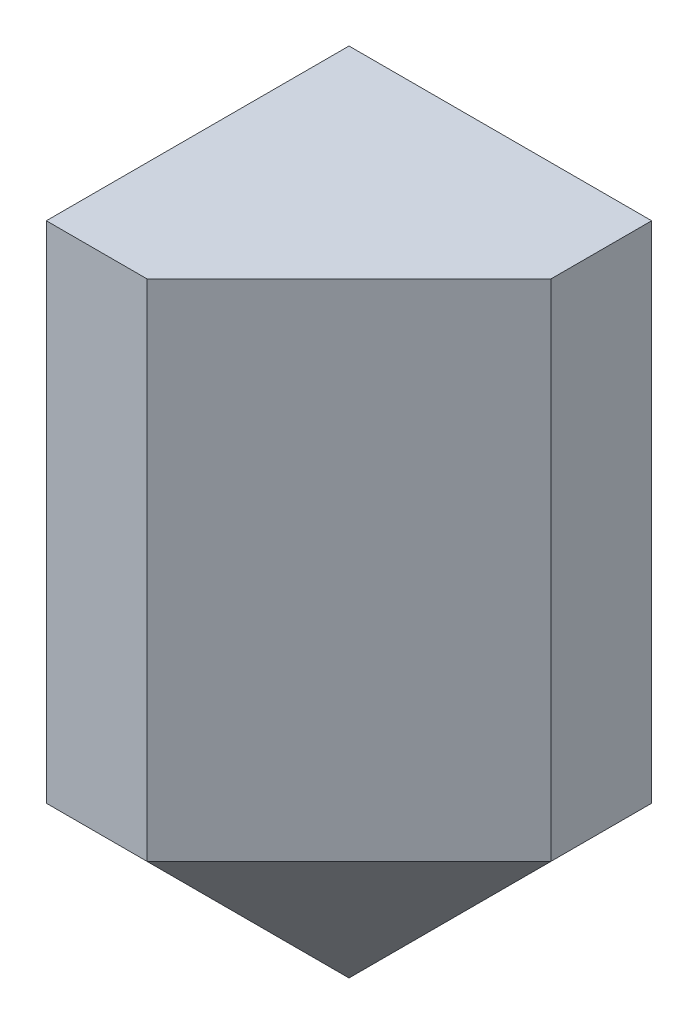
SolidWorks part; units mm, degrees
material "ABS"
ref_plane "Piano frontale" through (0, 0, 0) normal (0, 0, 1) x (1, 0, 0)
ref_plane "Piano superiore" through (0, 0, 0) normal (0, 1, 0) x (1, 0, 0)
ref_plane "Piano destro" through (0, 0, 0) normal (1, 0, 0) x (0, 0, -1)
sketch "Schizzo1" plane through (0, 0, 0) normal (0, 0, 1) x (1, 0, 0)
  line L1 (0, 0) -> (30, 0)
  line L2 (0, 0) -> (0, 40)
  line L3 (0, 40) -> (30, 40)
  line L4 (30, 0) -> (30, 40)
  dimension "D1" = 30
  dimension "D2" = 40
extrude "Estrusione-Estrusione1" add sketch "Schizzo1" along normal blind 30
chamfer "Smusso1" distance 20 angle 45 3 edges at (30, 20, 30) (30, 0, 15) (15, 0, 30)
sketch "Schizzo2" plane through (0, 40, 0) normal (0, 1, 0) x (1, 0, 0)
  line L0 (0, 0) -> (30, 0)
  line L1 (30, 0) -> (30, -10)
  line L2 (30, -10) -> (10, -30)
  line L3 (10, -30) -> (0, -30)
  line L4 (0, -30) -> (0, 0)
extrude "Estrusione-Estrusione2" add sketch "Schizzo2" along normal blind 30
hole_wizard "Foro per Vite M5-1" positions "Schizzo3" profile "Schizzo4" hole size "M5" standard "ISO"
sketch "Schizzo3" plane through (0, 0, 0) normal (-1, 0, 0) x (0, 0, 1)
  line L0 (14, 20) -> (14, 34) construction
  line L2 (0, 70) -> (0, 0) construction
  line L4 (14, 48) -> (14, 34) construction
  line L5 (0, 70) -> (30, 70) construction
  point P0 (14, 20)
  point P28 (14, 48)
  dimension "D1" = 14
  dimension "D2" = 22
  dimension "D3" = 14
  dimension "D4" = 14
sketch "Schizzo4" plane through (0, 20, 14) normal (0, 1, 0) x (0, 0, 1)
  line L0 (0, 0) -> (0, 14.6524)
  line L1 (0, 14.6524) -> (2.75, 13)
  line L2 (2.75, 13) -> (2.75, 0)
  line L5 (2.75, 0) -> (0, 0)
  line L10 (0, 14.6524) -> (-2.75, 13) construction
  line L11 (0, -6.35) -> (0, 107.95) construction
  dimension "Hole Dia." = 5.5
  dimension "Hole Depth" = 13
  dimension "Drill Angle" = 118
hole_wizard "Foro per Vite M5-2" positions "Schizzo3D1" profile "Schizzo5" hole size "M5" standard "ISO"
sketch3d "Schizzo3D1"
  line L4 (30, 70, 0) -> (0, 70, 0) construction
  line L5 (0, 70, 0) -> (0, 0, 0) construction
  point P2 (18, 20, 0)
  dimension "D1" = 50
  dimension "D2" = 18
sketch "Schizzo5" plane through (18, 20, 0) normal (1, 0, 0) x (0, 1, 0)
  line L0 (0, 0) -> (0, 14.6524)
  line L1 (0, 14.6524) -> (2.75, 13)
  line L2 (2.75, 13) -> (2.75, 0)
  line L5 (2.75, 0) -> (0, 0)
  line L10 (0, 14.6524) -> (-2.75, 13) construction
  line L11 (0, -6.35) -> (0, 107.95) construction
  dimension "Hole Dia." = 5.5
  dimension "Hole Depth" = 13
  dimension "Drill Angle" = 118
sketch "Schizzo6" plane through (0, 0, 0) normal (0, 0, -1) x (-1, 0, 0)
  line L0 (-30, 20) -> (-30, 70) construction
  line L1 (-30, 70) -> (0, 70) construction
  circle A0 centre (-15, 55) radius 7.5
  dimension "D1" = 15
  dimension "D3" = 15
  dimension "D2" = 15
extrude "Taglio-Estrusione1" cut sketch "Schizzo6" against normal blind 3
sketch "Schizzo7" plane through (0, 0, 3) normal (0, 0, -1) x (-1, 0, 0)
  point P0 (-15, 55)
hole_wizard "Foro per Vite M4-1" positions "Schizzo7" profile "Schizzo8" hole size "M4" standard "ISO"
sketch "Schizzo8" plane through (15, 55, 3) normal (1, 0, 0) x (0, 1, 0)
  line L0 (0, 0) -> (0, 11.3519)
  line L1 (0, 11.3519) -> (2.25, 10)
  line L2 (2.25, 10) -> (2.25, 0)
  line L5 (2.25, 0) -> (0, 0)
  line L10 (0, 11.3519) -> (-2.25, 10) construction
  line L11 (0, -6.35) -> (0, 107.95) construction
  dimension "Hole Dia." = 4.5
  dimension "Hole Depth" = 10
  dimension "Drill Angle" = 118
